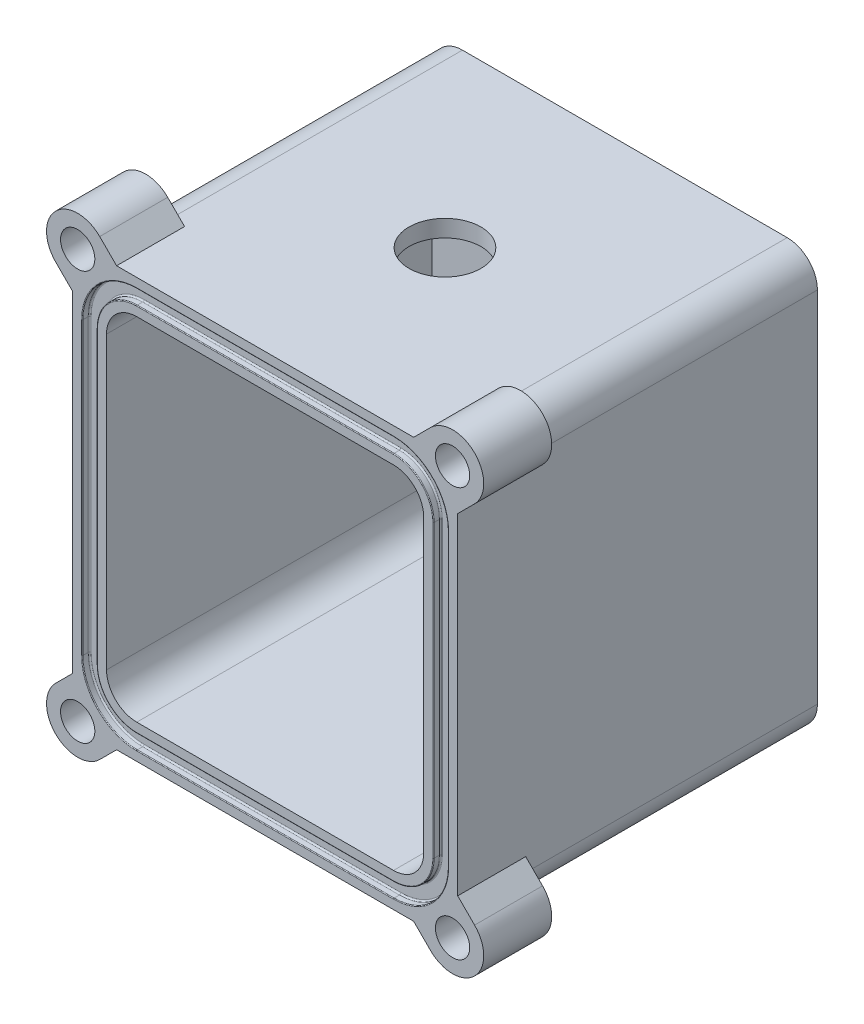
SolidWorks part; units mm, degrees
material "ABS"
ref_plane "X-Y Datum" through (0, 0, 0) normal (0, 0, 1) x (1, 0, 0)
ref_plane "X-Z Datum" through (0, 0, 0) normal (0, 1, 0) x (1, 0, 0)
ref_plane "Y-Z Datum" through (0, 0, 0) normal (1, 0, 0) x (0, 0, -1)
sketch "Sketch1" plane through (0, 0, 0) normal (0, 0, 1) x (1, 0, 0)
  line L0 (-34, -37) -> (-34, -16.68)
  line L1 (34, 37) -> (-34, 37)
  line L2 (34, 37) -> (34, -37)
  line L3 (34, -37) -> (-34, -37)
  line L5 (34, 37) -> (-34, -37) construction
  line L6 (34, -37) -> (-34, 37) construction
  line L7 (55.1739, 0) -> (-55.1739, 0) construction
  line L8 (-34, 37) -> (-34, 16.68)
  line L9 (-34, 16.68) -> (-34, -16.68)
  arc A0 (-34, -16.68) -> (-34, 16.68) centre (-14.8444, 0) cw construction
  point P0 (0, 0)
  dimension "D2" = 25.4
  dimension "D1" = 74
  dimension "D3" = 20.32
  dimension "D4" = 68
extrude "Boss-Extrude1" add sketch "Sketch1" along normal mid plane 63.5
shell "Shell1" thickness 6
fillet "Fillet1" radius 5.334 8 edges at (34, 37, 0) (34, -37, 0) (-34, -37, 0) (-34, 37, 0) (28, 31, 3) (28, -31, 3) (-28, -31, 3) (-28, 31, 3)
sketch "Sketch2" plane through (0, 0, 31.75) normal (0, 0, 1) x (1, 0, 0)
  line L21 (32.2827, -25.666) -> (32.2827, 25.666)
  line L22 (22.666, 35.2827) -> (-22.666, 35.2827)
  line L23 (-32.2827, 25.666) -> (-32.2827, -25.666)
  line L24 (-22.666, -35.2827) -> (22.666, -35.2827)
  line L25 (31, -25.666) -> (31, 25.666)
  line L26 (-22.666, -34) -> (22.666, -34)
  line L27 (-31, 25.666) -> (-31, -25.666)
  line L28 (22.666, 34) -> (-22.666, 34)
  line L29 (31, -25.666) -> (31, 25.666) construction
  line L30 (-22.666, -34) -> (22.666, -34) construction
  line L31 (-31, 25.666) -> (-31, -25.666) construction
  line L32 (22.666, 34) -> (-22.666, 34) construction
  line L33 (-29.7173, 25.666) -> (-29.7173, -25.666)
  line L34 (-22.666, -32.7173) -> (22.666, -32.7173)
  line L35 (29.7173, -25.666) -> (29.7173, 25.666)
  line L36 (22.666, 32.7173) -> (-22.666, 32.7173)
  arc A15 (32.2827, 25.666) -> (22.666, 35.2827) centre (22.666, 25.666) ccw
  arc A16 (-22.666, 35.2827) -> (-32.2827, 25.666) centre (-22.666, 25.666) ccw
  arc A17 (-32.2827, -25.666) -> (-22.666, -35.2827) centre (-22.666, -25.666) ccw
  arc A18 (22.666, -35.2827) -> (32.2827, -25.666) centre (22.666, -25.666) ccw
  arc A19 (31, 25.666) -> (22.666, 34) centre (22.666, 25.666) ccw
  arc A20 (22.666, -34) -> (31, -25.666) centre (22.666, -25.666) ccw
  arc A21 (-31, -25.666) -> (-22.666, -34) centre (-22.666, -25.666) ccw
  arc A22 (-22.666, 34) -> (-31, 25.666) centre (-22.666, 25.666) ccw
  arc A23 (31, 25.666) -> (22.666, 34) centre (22.666, 25.666) ccw construction
  arc A24 (22.666, -34) -> (31, -25.666) centre (22.666, -25.666) ccw construction
  arc A25 (-31, -25.666) -> (-22.666, -34) centre (-22.666, -25.666) ccw construction
  arc A26 (-22.666, 34) -> (-31, 25.666) centre (-22.666, 25.666) ccw construction
  arc A27 (-22.666, 32.7173) -> (-29.7173, 25.666) centre (-22.666, 25.666) ccw
  arc A28 (-29.7173, -25.666) -> (-22.666, -32.7173) centre (-22.666, -25.666) ccw
  arc A29 (22.666, -32.7173) -> (29.7173, -25.666) centre (22.666, -25.666) ccw
  arc A30 (29.7173, 25.666) -> (22.666, 32.7173) centre (22.666, 25.666) ccw
  dimension "D4" = 7.0513
  dimension "D5" = 2.5654
  dimension "D1" = 3
  dimension "D2" = 1.2827
  dimension "D3" = 1.2827
extrude "Cut-Extrude1" cut sketch "Sketch2" against normal blind 1.2954
fillet "Fillet2" radius 0.254 16 edges at (27.652, -30.652, 30.4546) (0, -32.7173, 30.4546) (-27.652, -30.652, 30.4546) (-29.7173, 0, 30.4546) (-27.652, 30.652, 30.4546) (0, 32.7173, 30.4546) (27.652, 30.652, 30.4546) (-29.466, 32.466, 30.4546) (0, 35.2827, 30.4546) (29.466, 32.466, 30.4546) (32.2827, 0, 30.4546) (29.466, -32.466, 30.4546) (0, -35.2827, 30.4546) (-29.466, -32.466, 30.4546) (29.7173, 0, 30.4546) (-32.2827, 0, 30.4546)
fillet "Fillet3" radius 0.127 16 edges at (-29.466, -32.466, 31.75) (-32.2827, 0, 31.75) (-29.466, 32.466, 31.75) (0, 35.2827, 31.75) (29.466, 32.466, 31.75) (32.2827, 0, 31.75) (29.466, -32.466, 31.75) (-27.652, -30.652, 31.75) (-29.7173, 0, 31.75) (-27.652, 30.652, 31.75) (0, 32.7173, 31.75) (27.652, 30.652, 31.75) (29.7173, 0, 31.75) (27.652, -30.652, 31.75) (0, -35.2827, 31.75) (0, -32.7173, 31.75)
sketch "Sketch3" plane through (0, 0, 31.75) normal (0, 0, 1) x (1, 0, 0)
  line L0 (22.666, -25.666) -> (37.7124, -40.7124) construction
  line L1 (29.2023, -39.9805) -> (26.2218, -37)
  line L2 (-28.666, -37) -> (28.666, -37) construction
  line L5 (34, -29.2218) -> (36.9805, -32.2023)
  line L6 (34, -31.666) -> (34, 31.666) construction
  arc A0 (22.666, -35.4097) -> (32.4097, -25.666) centre (22.666, -25.666) ccw construction
  arc A1 (22.666, -35.4097) -> (32.4097, -25.666) centre (22.666, -25.666) ccw
  circle A2 centre (33.0914, -36.0914) radius 3.025
  circle A3 centre (33.0914, -36.0914) radius 5.5
  point P7 (29.5558, -32.5558)
  dimension "D1" = 6.05
  dimension "D3" = 11
  dimension "D2" = 5
extrude "Boss-Extrude2" add sketch "Sketch3" against normal blind 12
sketch "Sketch4" plane through (0, 0, 31.75) normal (0, 0, 1) x (1, 0, 0)
  circle A0 centre (33.0914, -36.0914) radius 3.025 construction
  circle A1 centre (33.0914, -36.0914) radius 3.025
  dimension "D1" = 6.05
extrude "Cut-Extrude2" cut sketch "Sketch4" against normal blind 9
mirror "Mirror1" about plane through (0, 0, 0) normal (0, 1, 0) of "Cut-Extrude2", "Boss-Extrude2"
mirror "Mirror2" about plane through (0, 0, 0) normal (1, 0, 0) of "Mirror1", "Cut-Extrude2", "Boss-Extrude2"
sketch "Sketch6" plane through (0, 37, 0) normal (0, 1, 0) x (1, 0, 0)
  line L0 (28.666, 31.75) -> (-28.666, 31.75) construction
  line L1 (0, -31.75) -> (0, 31.75) construction
  line L2 (26.2218, -31.75) -> (-26.2218, -31.75) construction
  circle A0 centre (0, 0) radius 6.35
  circle A1 centre (0, 0) radius 11.43
  point P9 (0, 0)
  dimension "D1" = 12.7
  dimension "D2" = 22.86
extrude "Cut-Extrude3" cut sketch "Sketch6" against normal blind 6 contours A0 L1 | L1 A0
sketch "Sketch7" plane through (0, 31, 0) normal (0, -1, 0) x (1, 0, 0)
  circle A1 centre (0, 0) radius 11.43
  circle A2 centre (0, 0) radius 11.43
  circle A3 centre (0, 0) radius 6.35
  circle A4 centre (0, 0) radius 6.35
  dimension "D1" = 0
  dimension "D2" = 0
extrude "Cut-Extrude4" cut sketch "Sketch7" against normal blind 3
